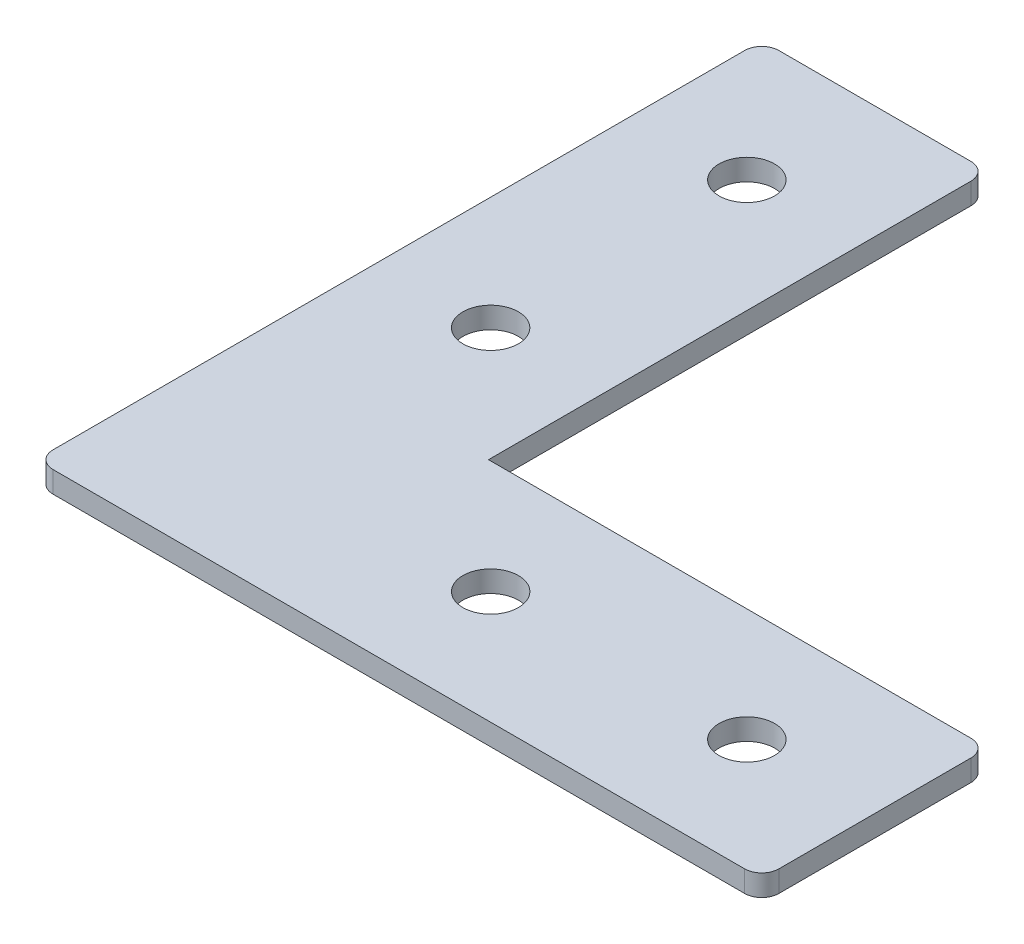
SolidWorks part; units mm, degrees
ref_plane "Front Plane" through (0, 0, 0) normal (0, 0, 1) x (1, 0, 0)
ref_plane "Top Plane" through (0, 0, 0) normal (0, 1, 0) x (1, 0, 0)
ref_plane "Right Plane" through (0, 0, 0) normal (1, 0, 0) x (0, 0, -1)
sketch "Sketch1" plane through (0, 0, 0) normal (0, 1, 0) x (1, 0, 0)
  line L1 (0, 0) -> (85, 0)
  line L2 (0, 0) -> (0, 14.012)
  line L3 (26.5, 26.5) -> (85, 26.5)
  line L4 (85, 0) -> (85, 26.5)
  line L5 (0, 0) -> (16.5589, 0)
  line L6 (0, 0) -> (0, 85)
  line L7 (0, 85) -> (26.5, 85)
  line L8 (26.5, 26.5) -> (26.5, 85)
  dimension "D1" = 85
  dimension "D2" = 85
  dimension "D3" = 26.5
  dimension "D4" = 26.5
extrude "Boss-Extrude1" add sketch "Sketch1" along normal blind 2.5 contours L6 L7 L8 L3 L4 L1
sketch "Sketch2" plane through (0, 2.5, 0) normal (0, 1, 0) x (1, 0, 0)
  line L0 (0, 85) -> (26.5, 85) construction
  line L1 (85, 0) -> (85, 26.5) construction
  circle A0 centre (13.25, 70) radius 3.25
  circle A1 centre (13.25, 40) radius 3.25
  circle A2 centre (70, 13.25) radius 3.25
  circle A3 centre (40, 13.25) radius 3.25
  point P11 (0, 0)
  point P13 (85, 13.25)
  point P14 (13.25, 85)
  dimension "D1" = 6.5
  dimension "D4" = 6.5
  dimension "D2" = 2
  dimension "15" = 15
  dimension "D3" = 30
  dimension "D5" = 15
  dimension "D7" = 30
  dimension "D6" = 2
extrude "Cut-Extrude1" cut sketch "Sketch2" against normal through all
fillet "Fillet1" radius 2 5 edges at (85, 1.25, 0) (85, 1.25, -26.5) (0, 1.25, 0) (0, 1.25, -85) (26.5, 1.25, -85)
